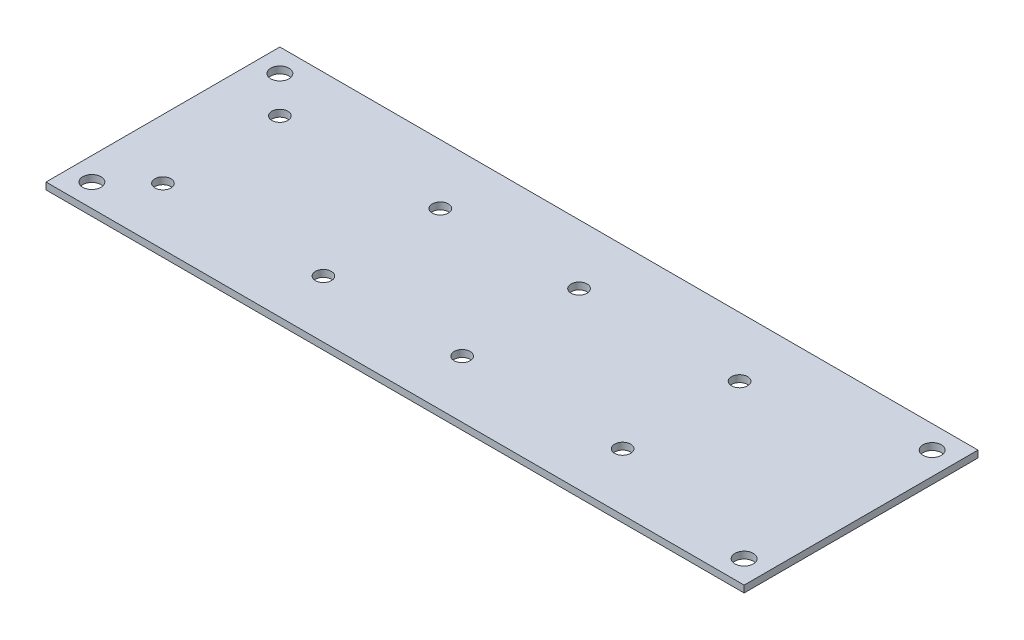
SolidWorks part; units mm, degrees
ref_plane "Front Plane" through (0, 0, 0) normal (0, 0, 1) x (1, 0, 0)
ref_plane "Top Plane" through (0, 0, 0) normal (0, 1, 0) x (1, 0, 0)
ref_plane "Right Plane" through (0, 0, 0) normal (1, 0, 0) x (0, 0, -1)
sketch "Sketch1" plane through (0, 0, 0) normal (0, 1, 0) x (1, 0, 0)
  line L0 (-63.125, 12.5) -> (37.125, 12.5) construction
  line L1 (-76.125, -25.5) -> (76.125, -25.5)
  line L2 (-76.125, -25.5) -> (-76.125, 25.5)
  line L3 (-76.125, 25.5) -> (76.125, 25.5)
  line L4 (76.125, -25.5) -> (76.125, 25.5)
  line L5 (-76.125, -25.5) -> (76.125, 25.5) construction
  line L6 (-76.125, 25.5) -> (76.125, -25.5) construction
  line L7 (-63.125, -13) -> (37.125, -13) construction
  circle A0 centre (-63.125, 12.5) radius 1.75
  circle A1 centre (-63.125, -13) radius 1.75
  circle A2 centre (-28.125, 12.5) radius 1.75
  circle A3 centre (-28.125, -13) radius 1.75
  circle A4 centre (2.125, 12.5) radius 1.75
  circle A5 centre (37.125, 12.5) radius 1.75
  circle A6 centre (37.125, -13) radius 1.75
  circle A7 centre (2.125, -13) radius 1.75
  circle A8 centre (-71.125, 20.5) radius 2
  circle A9 centre (71.125, 20.5) radius 2
  circle A10 centre (71.125, -20.5) radius 2
  circle A11 centre (-71.125, -20.5) radius 2
  point P0 (0, 0)
  point P30 (0, 0)
  point P31 (0, 0)
  point P32 (0, 0)
  point P33 (0, 0)
  point P34 (0, 0)
  point P35 (-71.125, -21.2127)
  point P36 (70.6839, 20.5)
  dimension "D3" = 3.5
  dimension "D10" = 4
  dimension "D1" = 51
  dimension "D2" = 152.25
  dimension "D4" = 13
  dimension "D5" = 12.5
  dimension "D6" = 13
  dimension "D7" = 35
  dimension "D8" = 35
  dimension "D9" = 39
  dimension "D11" = 5
  dimension "D12" = 5
  dimension "D13" = 5
  dimension "D14" = 5
extrude "Boss-Extrude1" add sketch "Sketch1" against normal blind 1.5
